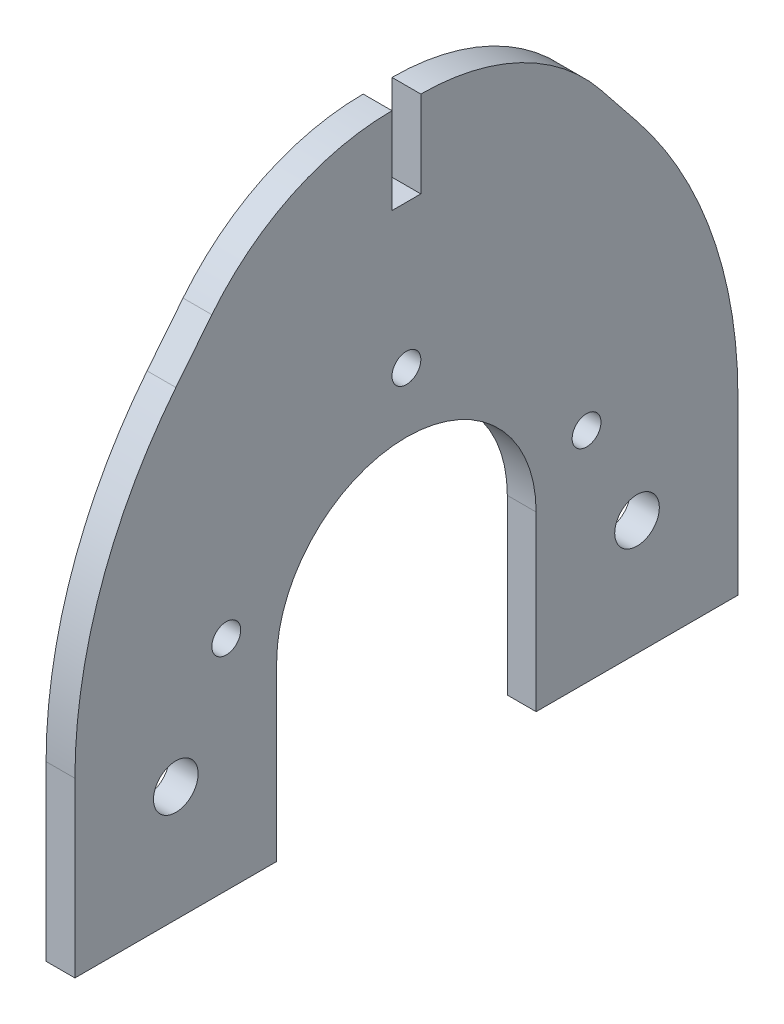
SolidWorks part; units mm, degrees
material "6061 Alloy"
ref_plane "Front Plane" through (0, 0, 0) normal (0, 0, 1) x (1, 0, 0)
ref_plane "Top Plane" through (0, 0, 0) normal (0, 1, 0) x (1, 0, 0)
ref_plane "Right Plane" through (0, 0, 0) normal (1, 0, 0) x (0, 0, -1)
sketch "Sketch1" plane through (0, 0, 0) normal (1, 0, 0) x (0, 0, -1)
  line L0 (1.5875, 46.2199) -> (1.5875, 36.6949)
  line L1 (1.5875, 36.6949) -> (-1.5875, 36.6949)
  line L2 (0, 0) -> (0, 73.524) construction
  line L3 (-1.5875, 46.2199) -> (-1.5875, 36.6949)
  line L4 (25.4, 0) -> (-25.4, 0) construction
  line L5 (21.4275, 36.6797) -> (25.3924, 31.7198)
  line L6 (-21.4275, 36.6797) -> (-25.3924, 31.7198)
  line L7 (36.5125, 0) -> (36.5125, -19.05)
  line L8 (36.5125, -19.05) -> (14.2875, -19.05)
  line L9 (14.2875, -19.05) -> (14.2875, 0)
  line L10 (-14.2875, 0) -> (-14.2875, -19.05)
  line L11 (-14.2875, -19.05) -> (-36.5125, -19.05)
  line L12 (-36.5125, -19.05) -> (-36.5125, 0)
  arc A0 (14.2875, 0) -> (-14.2875, 0) centre (0, 0) ccw
  arc A3 (36.5125, 0) -> (25.3924, 31.7198) centre (-14.2875, 0) ccw
  arc A5 (21.4275, 36.6797) -> (1.5875, 46.2199) centre (1.5875, 20.8199) ccw
  arc A7 (-36.5125, 0) -> (-25.3924, 31.7198) centre (14.2875, 0) cw
  arc A10 (-21.4275, 36.6797) -> (-1.5875, 46.2199) centre (-1.5875, 20.8199) cw
  circle A11 centre (25.4, 0) radius 2.5797 construction
  circle A12 centre (-25.4, 0) radius 2.5797 construction
  point P18 (0, 36.6949)
  point P30 (0, 0)
  dimension "D1" = 28.575
  dimension "D3" = 25.4
  dimension "D4" = 6.35
  dimension "D5" = 19.05
  dimension "D6" = 50.8
  dimension "D7" = 22.225
  dimension "D9" = 5.1594
  dimension "D2" = 3.175
  dimension "D8" = 50.8
  dimension "D12" = 9.525
extrude "Boss-Extrude1" add sketch "Sketch1" along normal blind 3.175
hole_wizard "#10 (0.1935) Diameter Hole1" positions "Sketch2" profile "Sketch3" hole size "#10" standard "ANSI Inch"
sketch "Sketch2" plane through (0, 0, 0) normal (-1, 0, 0) x (0, 0, 1)
  line L2 (-25.4, -6.35) -> (25.4, -6.35) construction
  point P0 (-25.4, -6.35)
  point P2 (25.4, -6.35)
  point P29 (0, -6.35)
  dimension "D1" = 50.8
  dimension "D2" = 6.35
sketch "Sketch3" plane through (0, -6.35, -25.4) normal (0, 1, 0) x (0, 0, 1)
  line L0 (0, 0) -> (0, 20.4786)
  line L1 (0, 20.4786) -> (2.4574, 19.002)
  line L2 (2.4574, 19.002) -> (2.4574, 0)
  line L5 (2.4574, 0) -> (0, 0)
  line L10 (0, 20.4786) -> (-2.4574, 19.002) construction
  line L11 (0, -6.35) -> (0, 107.95) construction
  dimension "Hole Dia." = 4.9149
  dimension "Hole Depth" = 19.002
  dimension "Drill Angle" = 118
sketch "Sketch4" plane through (3.175, 0, 0) normal (1, 0, 0) x (0, 0, -1)
  circle A0 centre (-19.8426, 5.0165) radius 1.5875 construction
  circle A1 centre (0, 20.8915) radius 1.5875 construction
  circle A2 centre (19.8426, 5.0165) radius 1.5875 construction
  circle A3 centre (-19.8426, 5.0165) radius 1.5875
  circle A4 centre (0, 20.8915) radius 1.5875
  circle A5 centre (19.8426, 5.0165) radius 1.5875
extrude "Cut-Extrude1" cut sketch "Sketch4" against normal through all
